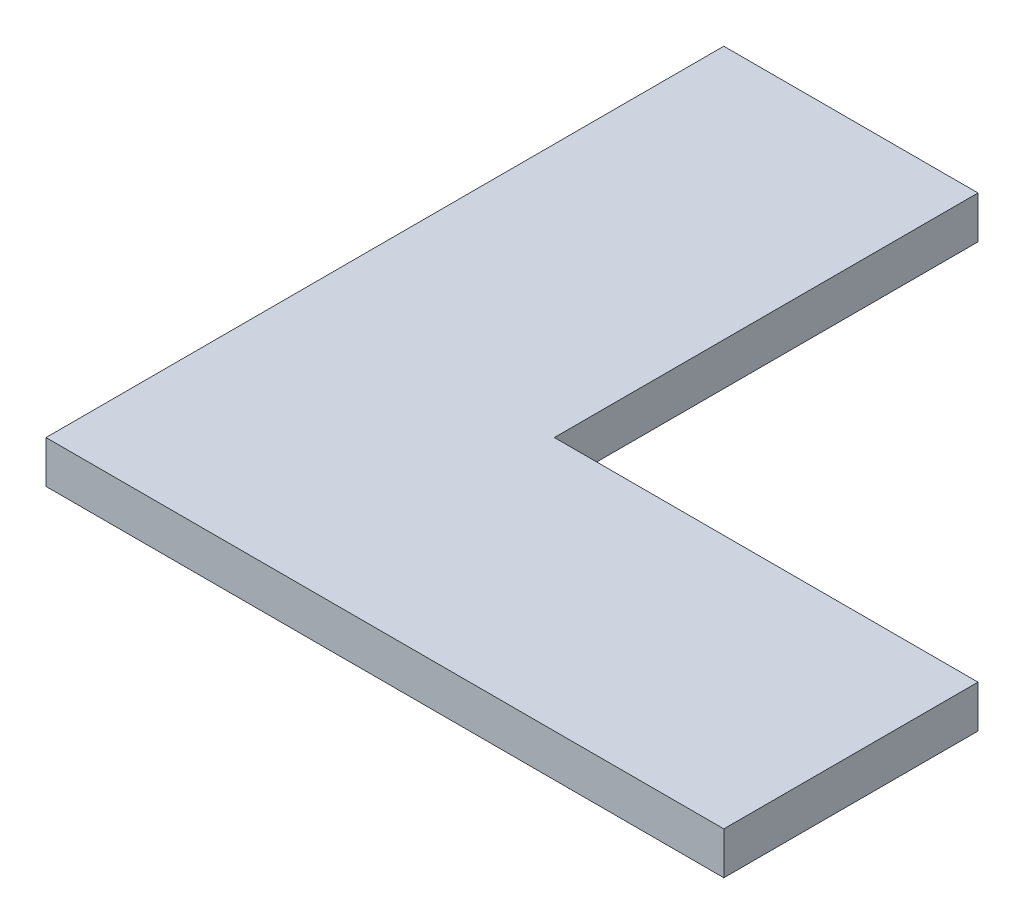
SolidWorks part; units mm, degrees
ref_plane "Front Plane" through (0, 0, 0) normal (0, 0, 1) x (1, 0, 0)
ref_plane "Top Plane" through (0, 0, 0) normal (0, 1, 0) x (1, 0, 0)
ref_plane "Right Plane" through (0, 0, 0) normal (1, 0, 0) x (0, 0, -1)
sketch "Sketch1" plane through (0, 0, 0) normal (0, 1, 0) x (1, 0, 0)
  line L0 (-40, 40) -> (-40, -40)
  line L1 (-40, -40) -> (40, -40)
  line L2 (40, -40) -> (40, -10)
  line L3 (40, -10) -> (-10, -10)
  line L4 (-10, -10) -> (-10, 40)
  line L5 (-10, 40) -> (-40, 40)
  point P5 (-40, 0)
  point P8 (0, -40)
  dimension "D1" = 50
  dimension "D2" = 30
extrude "Boss-Extrude1" add sketch "Sketch1" along normal mid plane 5
